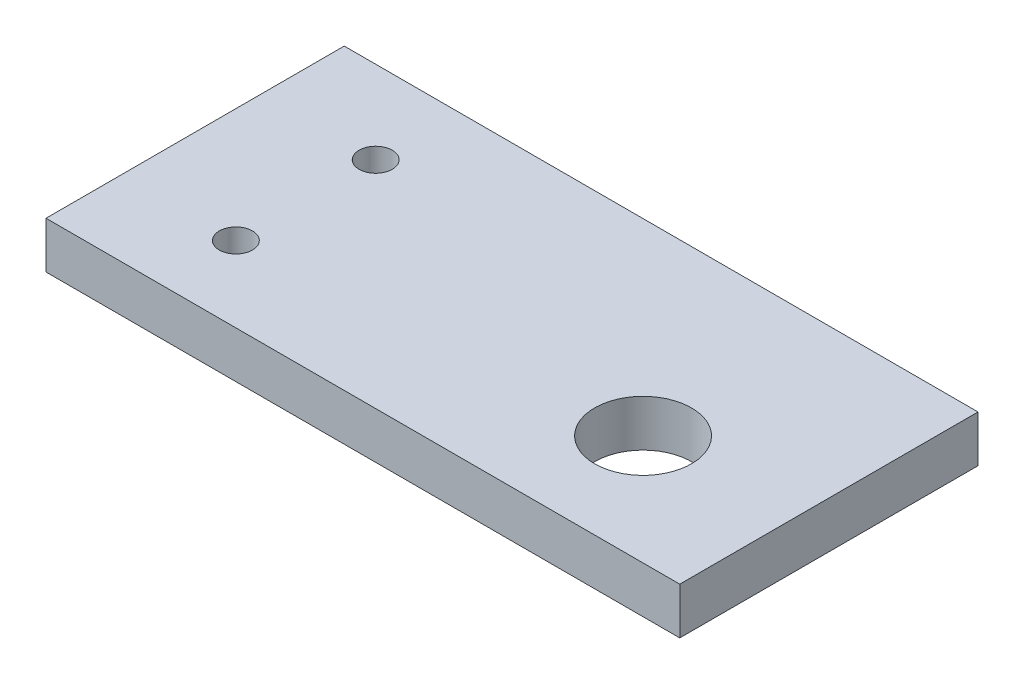
SolidWorks part; units mm, degrees
ref_plane "Front Plane" through (0, 0, 0) normal (0, 0, 1) x (1, 0, 0)
ref_plane "Top Plane" through (0, 0, 0) normal (0, 1, 0) x (1, 0, 0)
ref_plane "Right Plane" through (0, 0, 0) normal (1, 0, 0) x (0, 0, -1)
sketch "Sketch1" plane through (0, 0, 0) normal (0, 1, 0) x (1, 0, 0)
  line L1 (0, 0) -> (43.18, 0)
  line L3 (0, 20.32) -> (43.18, 20.32)
  line L4 (43.18, 0) -> (43.18, 20.32)
  line L6 (0, 0) -> (0, 20.32)
  circle A0 centre (33.18, 7.5) radius 3.3
  dimension "D3" = 6.6
  dimension "D1" = 20.32
  dimension "D2" = 43.18
  dimension "D8" = 7.5
  dimension "D9" = 10
extrude "Boss-Extrude1" add sketch "Sketch1" along normal blind 3.175
sketch "Sketch2" plane through (0, 3.175, 0) normal (0, 1, 0) x (1, 0, 0)
  line L0 (0, 0) -> (43.18, 0) construction
  line L1 (43.18, 0) -> (43.18, 20.32) construction
  circle A0 centre (7.78, 5.1562) radius 1.1303
  circle A1 centre (7.78, 14.6812) radius 1.1303
  dimension "D1" = 2.2606
  dimension "D2" = 5.1562
  dimension "D3" = 35.4
  dimension "D4" = 9.525
extrude "Cut-Extrude1" cut sketch "Sketch2" against normal through all
